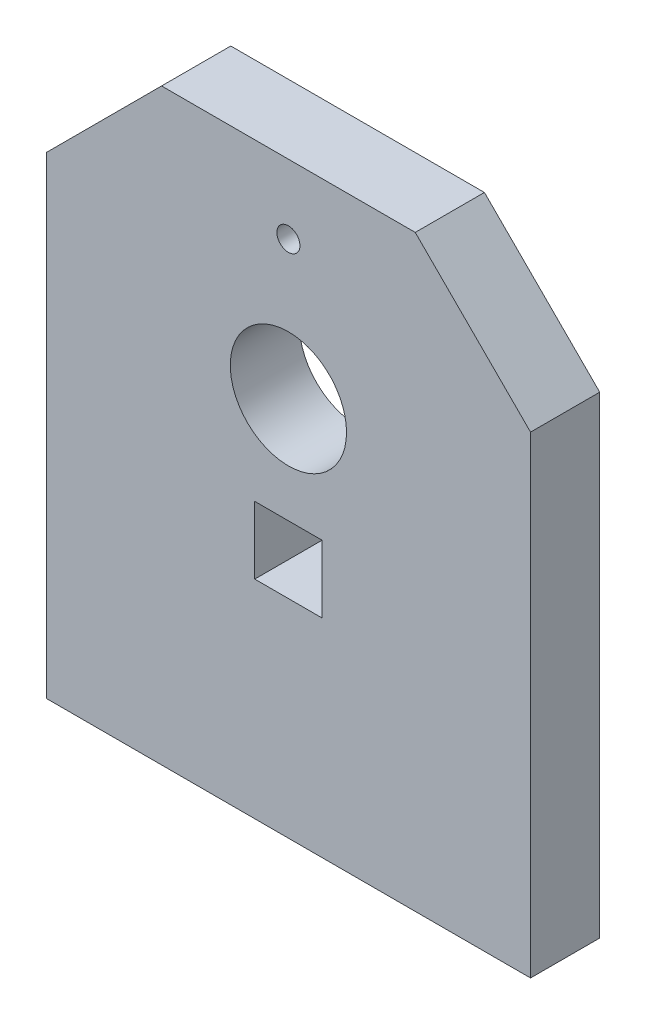
SolidWorks part; units mm, degrees
ref_plane "Front Plane" through (0, 0, 0) normal (0, 0, 1) x (1, 0, 0)
ref_plane "Top Plane" through (0, 0, 0) normal (0, 1, 0) x (1, 0, 0)
ref_plane "Right Plane" through (0, 0, 0) normal (1, 0, 0) x (0, 0, -1)
sketch "Sketch1" plane through (0, 0, 0) normal (0, 0, 1) x (1, 0, 0)
  line L0 (8.5483, 11.7097) -> (13.5483, 6.7097)
  line L1 (-7.4517, 11.7097) -> (13.5483, 11.7097)
  line L2 (-7.4517, 11.7097) -> (-7.4517, -13.7903)
  line L3 (-7.4517, -13.7903) -> (13.5483, -13.7903)
  line L4 (13.5483, 11.7097) -> (13.5483, -13.7903)
  line L5 (3.0483, 11.7097) -> (3.0483, 6.905) construction
  line L6 (-2.4517, 11.7097) -> (-7.4517, 6.7097)
  line L8 (1.5883, -1.8703) -> (4.5083, -1.8703)
  line L9 (1.5883, -1.8703) -> (1.5883, -4.7903)
  line L10 (1.5883, -4.7903) -> (4.5083, -4.7903)
  line L11 (4.5083, -1.8703) -> (4.5083, -4.7903)
  circle A0 centre (3.0483, 2.7097) radius 2.52
  circle A1 centre (3.0483, 8.7097) radius 0.5
  point P16 (3.0483, -1.8703)
  dimension "D5" = 5.04
  dimension "D6" = 16.5
  dimension "D11" = 1
  dimension "D12" = 6
  dimension "D1" = 25.5
  dimension "D2" = 21
  dimension "D3" = 5
  dimension "D4" = 5
  dimension "D7" = 2.92
  dimension "D8" = 2.92
  dimension "D9" = 9
  dimension "D10" = 10.5
extrude "Boss-Extrude1" add sketch "Sketch1" along normal blind 3
